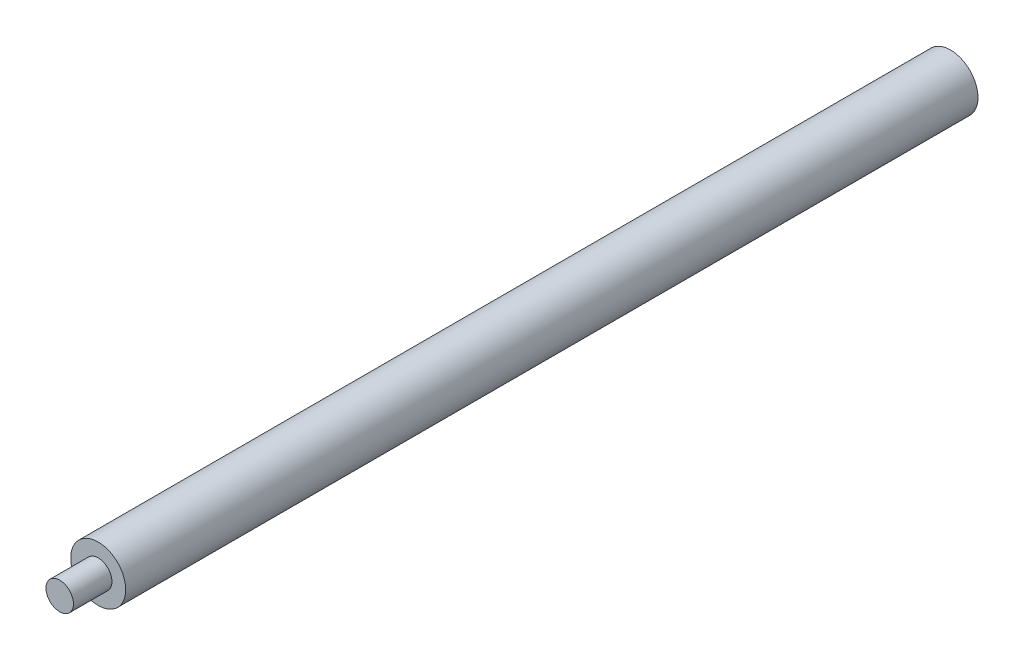
SolidWorks part; units mm, degrees
ref_plane "Front Plane" through (0, 0, 0) normal (0, 0, 1) x (1, 0, 0)
ref_plane "Top Plane" through (0, 0, 0) normal (0, 1, 0) x (1, 0, 0)
ref_plane "Right Plane" through (0, 0, 0) normal (1, 0, 0) x (0, 0, -1)
sketch "Sketch1" plane through (0, 0, 0) normal (0, 0, 1) x (1, 0, 0)
  circle A0 centre (0, 0) radius 5
  dimension "D1" = 10
extrude "Boss-Extrude1" add sketch "Sketch1" along normal blind 155
sketch "Sketch2" plane through (0, 0, 155) normal (0, 0, 1) x (1, 0, 0)
  circle A0 centre (0, 0) radius 2.5
  dimension "D1" = 5
extrude "Boss-Extrude2" add sketch "Sketch2" along normal blind 7
sketch "Sketch3" plane through (0, 0, 0) normal (0, 0, -1) x (-1, 0, 0)
  circle A0 centre (0, 0) radius 3
  dimension "D1" = 6
extrude "Cut-Extrude1" cut sketch "Sketch3" against normal blind 10
